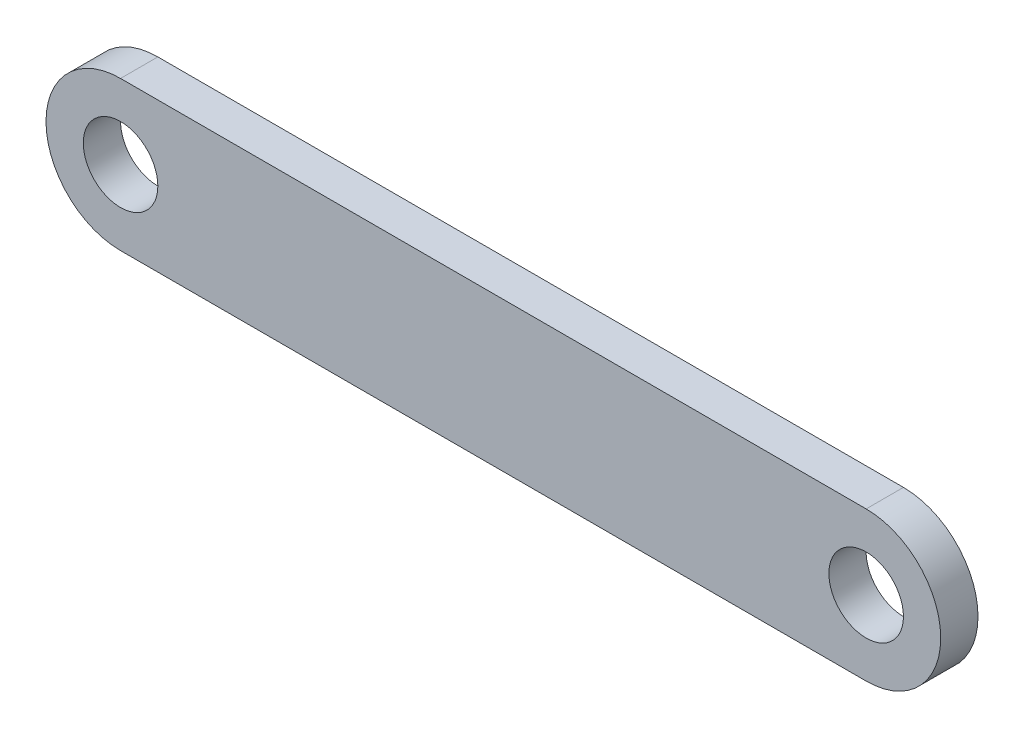
SolidWorks part; units mm, degrees
ref_plane "Alzado" through (0, 0, 0) normal (0, 0, 1) x (1, 0, 0)
ref_plane "Planta" through (0, 0, 0) normal (0, 1, 0) x (1, 0, 0)
ref_plane "Vista lateral" through (0, 0, 0) normal (1, 0, 0) x (0, 0, -1)
sketch "Croquis1" plane through (0, 0, 0) normal (0, 0, 1) x (1, 0, 0)
  line L0 (-50, 0) -> (50, 0) construction
  line L1 (-50, 10) -> (50, 10)
  line L2 (-50, -10) -> (50, -10)
  arc A0 (-50, 10) -> (-50, -10) centre (-50, 0) ccw
  arc A1 (50, -10) -> (50, 10) centre (50, 0) ccw
  circle A2 centre (-50, 0) radius 5
  circle A3 centre (50, 0) radius 5
  point P2 (0, 0)
  dimension "D3" = 10
  dimension "D1" = 100
  dimension "D2" = 20
extrude "Saliente-Extruir1" add sketch "Croquis1" along normal blind 5
